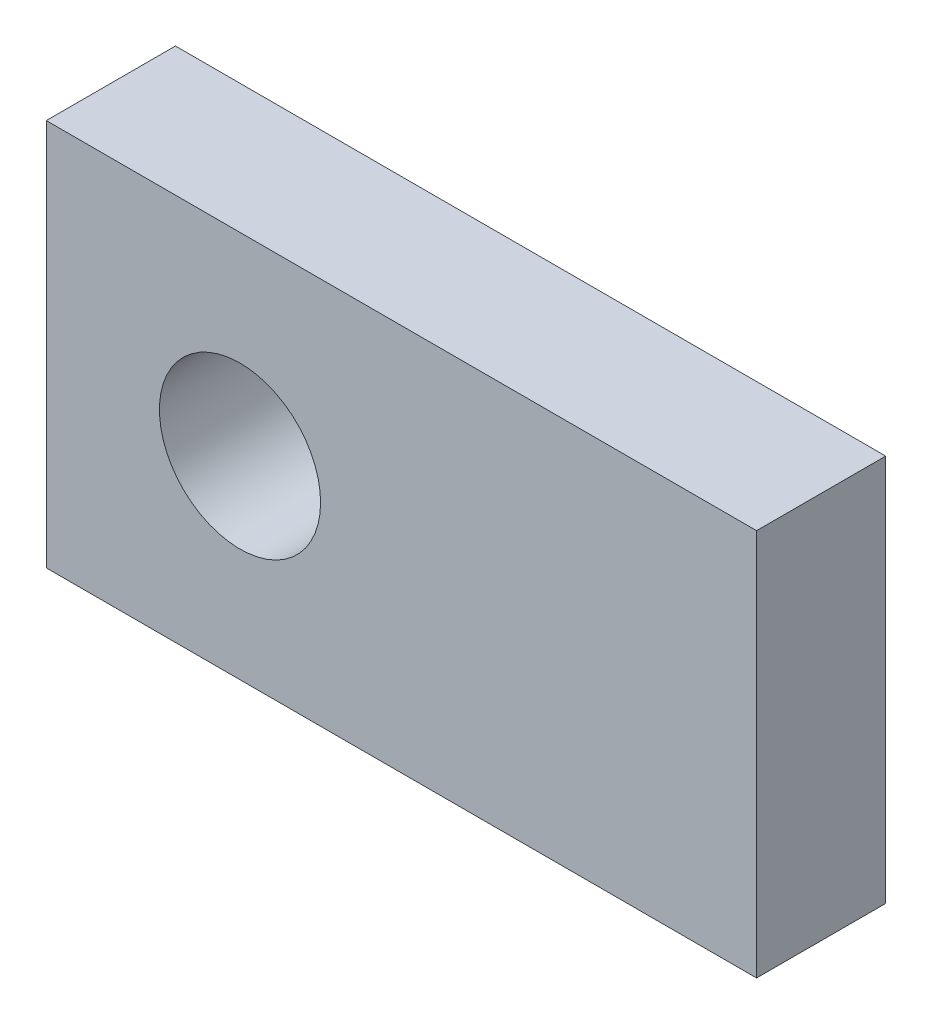
SolidWorks part; units mm, degrees
ref_plane "Front Plane" through (0, 0, 0) normal (0, 0, 1) x (1, 0, 0)
ref_plane "Top Plane" through (0, 0, 0) normal (0, 1, 0) x (1, 0, 0)
ref_plane "Right Plane" through (0, 0, 0) normal (1, 0, 0) x (0, 0, -1)
sketch "Sketch1" plane through (0, 0, 0) normal (0, 0, 1) x (1, 0, 0)
  line L1 (17.4625, -9.525) -> (-17.4625, -9.525)
  line L2 (17.4625, -9.525) -> (17.4625, 9.525)
  line L3 (17.4625, 9.525) -> (-17.4625, 9.525)
  line L4 (-17.4625, -9.525) -> (-17.4625, 9.525)
  line L5 (17.4625, -9.525) -> (-17.4625, 9.525) construction
  line L6 (17.4625, 9.525) -> (-17.4625, -9.525) construction
  circle A0 centre (-7.9375, 0) radius 3.9624
  point P0 (0, 0)
  point P8 (0, 0)
  dimension "D3" = 9.525
  dimension "D4" = 7.9248
  dimension "D1" = 34.925
  dimension "D2" = 19.05
extrude "Boss-Extrude1" add sketch "Sketch1" along normal blind 6.35
